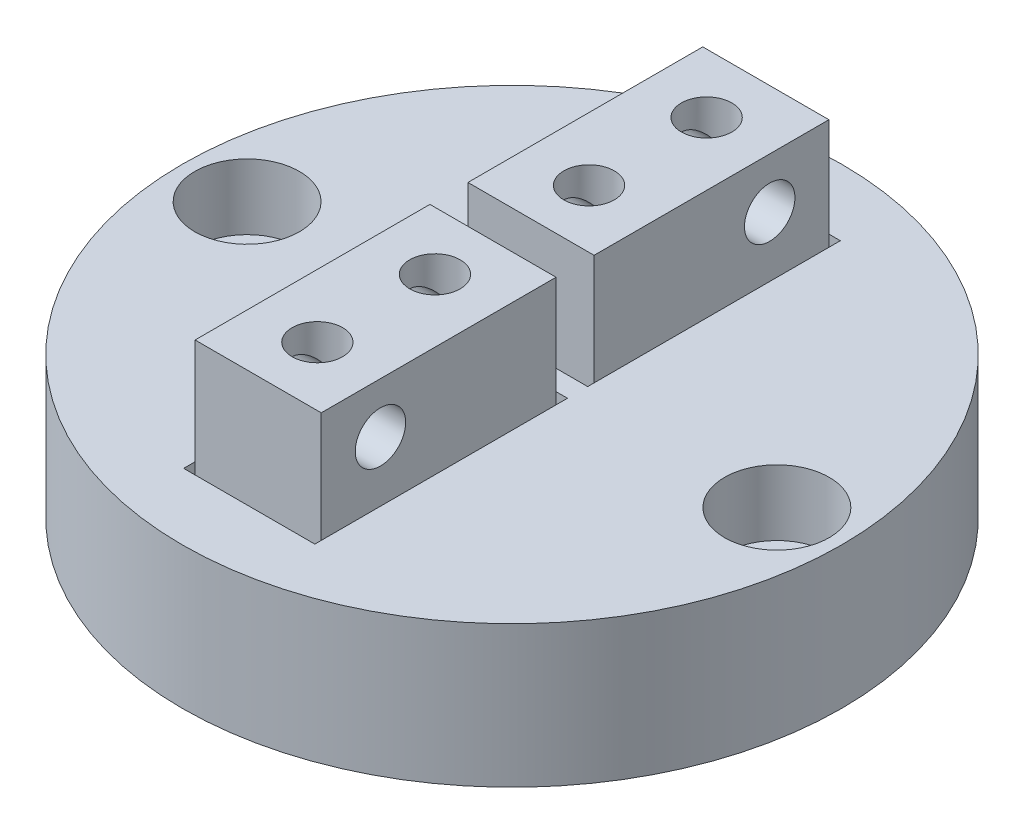
SolidWorks part; units mm, degrees
ref_plane "Front Plane" through (0, 0, 0) normal (0, 0, 1) x (1, 0, 0)
ref_plane "Top Plane" through (0, 0, 0) normal (0, 1, 0) x (1, 0, 0)
ref_plane "Right Plane" through (0, 0, 0) normal (1, 0, 0) x (0, 0, -1)
sketch "Sketch1" plane through (0, 0, 0) normal (0, 1, 0) x (1, 0, 0)
  circle A0 centre (0, 0) radius 24.892
  dimension "D1" = 49.784
extrude "Boss-Extrude1" add sketch "Sketch1" along normal blind 10.6934
hole_wizard "CBORE for #4 Binding Head Machine Screw1" positions "Sketch3" profile "Sketch2" counterbore size "#4" standard "ANSI Inch" end condition through all
sketch "Sketch3" plane through (0, 0, 0) normal (0, -1, 0) x (-1, 0, 0)
  line L0 (0, -14.6939) -> (0, 14.6939) construction
  point P0 (0, -14.6939)
  point P2 (0, 14.6939)
  dimension "D1" = 29.3878
sketch "Sketch2" plane through (0, 0, 14.6939) normal (1, 0, 0) x (0, 0, -1)
  line L0 (0, 0) -> (0, 10.6934)
  line L1 (0, 10.6934) -> (2.9845, 10.6934)
  line L3 (2.9845, 10.6934) -> (2.9845, 4.2164)
  line L4 (2.9845, 4.2164) -> (4.826, 4.2164)
  line L5 (4.826, 4.2164) -> (4.826, 0)
  line L7 (4.826, 0) -> (0, 0)
  line L11 (0, -6.35) -> (0, 107.95) construction
  dimension "Thru Hole Dia." = 5.969
  dimension "Thru Hole Depth" = 10.6934
  dimension "C'Bore Dia." = 9.652
  dimension "C'Bore Depth" = 4.2164
hole_wizard "CBORE for #4 Binding Head Machine Screw2" positions "Sketch5" profile "Sketch4" counterbore size "#4" standard "ANSI Inch" end condition through all
sketch "Sketch5" plane through (0, 10.6934, 0) normal (0, 1, 0) x (1, 0, 0)
  line L0 (-20, 0) -> (20, 0) construction
  point P0 (-20, 0)
  point P2 (20, 0)
  dimension "D1" = 40
sketch "Sketch4" plane through (-20, 10.6934, 0) normal (1, 0, 0) x (0, 0, 1)
  line L0 (0, 0) -> (0, 10.6934)
  line L1 (0, 10.6934) -> (2.6924, 10.6934)
  line L3 (2.6924, 10.6934) -> (2.6924, 4.953)
  line L4 (2.6924, 4.953) -> (3.9497, 4.953)
  line L5 (3.9497, 4.953) -> (3.9497, 0)
  line L7 (3.9497, 0) -> (0, 0)
  line L11 (0, -6.35) -> (0, 107.95) construction
  dimension "Thru Hole Dia." = 5.3848
  dimension "Thru Hole Depth" = 10.6934
  dimension "C'Bore Dia." = 7.8994
  dimension "C'Bore Depth" = 4.953
sketch "Sketch6" plane through (0, 0, 0) normal (0, 1, 0) x (1, 0, 0)
  line L0 (0, -5.8166) -> (0, 5.8166) construction
  circle A0 centre (0, -5.8166) radius 2.1971
  circle A1 centre (0, 5.8166) radius 2.1971
  dimension "D1" = 11.6332
  dimension "D2" = 4.3942
extrude "Cut-Extrude1" cut sketch "Sketch6" along normal through all
sketch "Sketch7" plane through (0, 10.6934, 0) normal (0, 1, 0) x (1, 0, 0)
  line L0 (0, -5.8814) -> (0, 5.8814) construction
  line L1 (4.953, 0.762) -> (-4.953, 0.762)
  line L2 (4.953, 0.762) -> (4.953, 19.8374)
  line L3 (4.953, 19.8374) -> (-4.953, 19.8374)
  line L4 (-4.953, 0.762) -> (-4.953, 19.8374)
  line L5 (4.953, 0.762) -> (-4.953, 19.8374) construction
  line L6 (4.953, 19.8374) -> (-4.953, 0.762) construction
  line L7 (-5.8814, 0) -> (5.8814, 0) construction
  point P0 (0, 10.2997)
  dimension "D1" = 9.906
  dimension "D2" = 19.0754
  dimension "D3" = 0.762
extrude "Cut-Extrude2" cut sketch "Sketch7" against normal blind 1.3716
mirror "Mirror1" about plane through (0, 0, 0) normal (0, 0, 1) of "Cut-Extrude2"
sketch "Sketch8" plane through (0, 9.3218, 0) normal (0, 1, 0) x (1, 0, 0)
  line L1 (-4.7625, 1.4351) -> (4.7625, 1.4351)
  line L2 (-4.7625, 1.4351) -> (-4.7625, 19.1643)
  line L3 (-4.7625, 19.1643) -> (4.7625, 19.1643)
  line L4 (4.7625, 1.4351) -> (4.7625, 19.1643)
  line L5 (-4.7625, 1.4351) -> (4.7625, 19.1643) construction
  line L6 (-4.7625, 19.1643) -> (4.7625, 1.4351) construction
  point P0 (0, 10.2997)
  dimension "D1" = 9.525
  dimension "D2" = 17.7292
extrude "Boss-Extrude2" add sketch "Sketch8" along normal blind 9.525 separate body
sketch "Sketch9" plane through (0, 0, 0) normal (0, 1, 0) x (1, 0, 0)
  circle A0 centre (0, 0) radius 0.9144
  dimension "D1" = 1.8288
extrude "Cut-Extrude3" cut sketch "Sketch9" along normal blind 6.7
sketch "Sketch10" plane through (0, 10.6934, 0) normal (0, 1, 0) x (1, 0, 0)
  circle A0 centre (0, 0) radius 0.6985
  dimension "D1" = 1.397
extrude "Cut-Extrude11" cut sketch "Sketch10" against normal through all
sketch "Sketch11" plane through (0, 18.8468, 0) normal (0, 1, 0) x (1, 0, 0)
  circle A0 centre (0, 14.6939) radius 1.905
  circle A1 centre (0, 5.8166) radius 1.905
  dimension "D1" = 3.81
extrude "Cut-Extrude12" cut sketch "Sketch11" against normal through all
sketch "Sketch12" plane through (-4.7625, 0, 0) normal (-1, 0, 0) x (0, 0, 1)
  line L0 (-5.8166, 9.3218) -> (-5.8166, 18.8468) construction
  circle A0 centre (-5.8166, 15.0368) radius 1.905
  dimension "D1" = 3.81
  dimension "D2" = 3.81
extrude "Cut-Extrude13" cut sketch "Sketch12" against normal up to surface (4.7625 mm away) up to plane "Right Plane"
sketch "Sketch13" plane through (-4.7625, 0, 0) normal (-1, 0, 0) x (0, 0, 1)
  line L0 (-14.6939, 9.3218) -> (-14.6939, 18.8468) construction
  line L1 (-5.8166, 15.0368) -> (-14.6939, 15.0368) construction
  circle A0 centre (-14.6939, 15.0368) radius 1.905
  dimension "D1" = 3.81
extrude "Cut-Extrude14" cut sketch "Sketch13" against normal through all
mirror "Mirror2" about plane through (0, 0, 0) normal (0, 0, 1) of bodies 112
